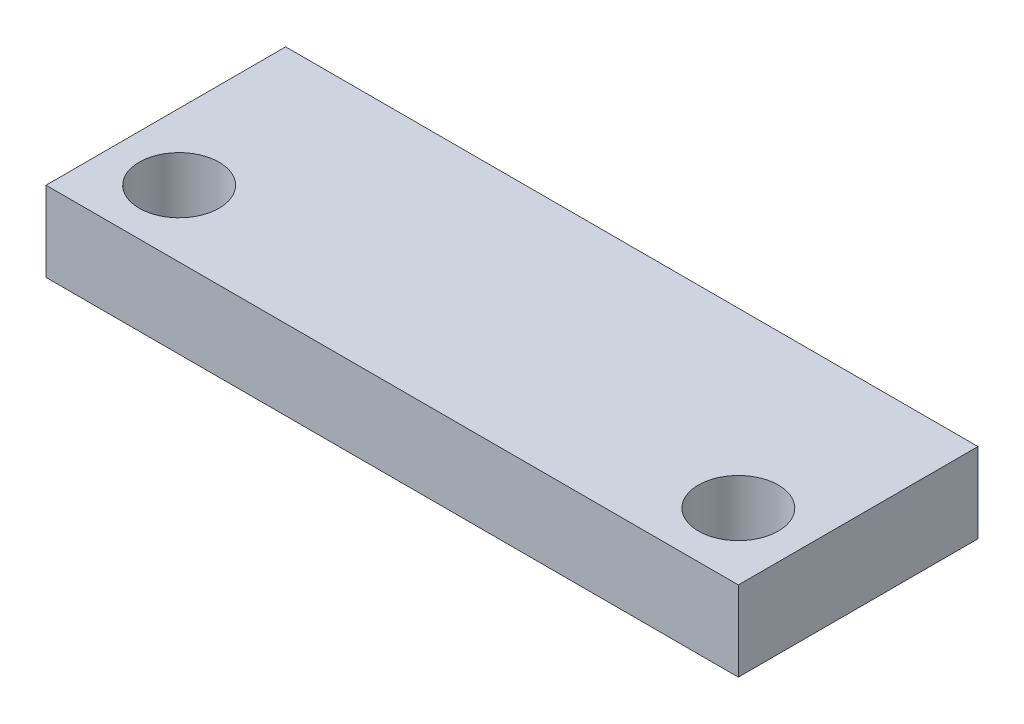
SolidWorks part; units mm, degrees
ref_plane "Płaszczyzna przednia" through (0, 0, 0) normal (0, 0, 1) x (1, 0, 0)
ref_plane "Płaszczyzna górna" through (0, 0, 0) normal (0, 1, 0) x (1, 0, 0)
ref_plane "Płaszczyzna prawa" through (0, 0, 0) normal (1, 0, 0) x (0, 0, -1)
sketch "Szkic1" plane through (0, 0, 0) normal (0, 1, 0) x (1, 0, 0)
  line L1 (0, 0) -> (26, 0)
  line L2 (0, 0) -> (0, 9)
  line L3 (0, 9) -> (26, 9)
  line L4 (26, 0) -> (26, 9)
  circle A3 centre (2.5, 2.5) radius 1.5
  circle A4 centre (23.5, 2.5) radius 1.5
  dimension "D1" = 3
  dimension "D2" = 2.5
extrude "Dodanie-wyciągnięcie1" add sketch "Szkic1" along normal blind 3
